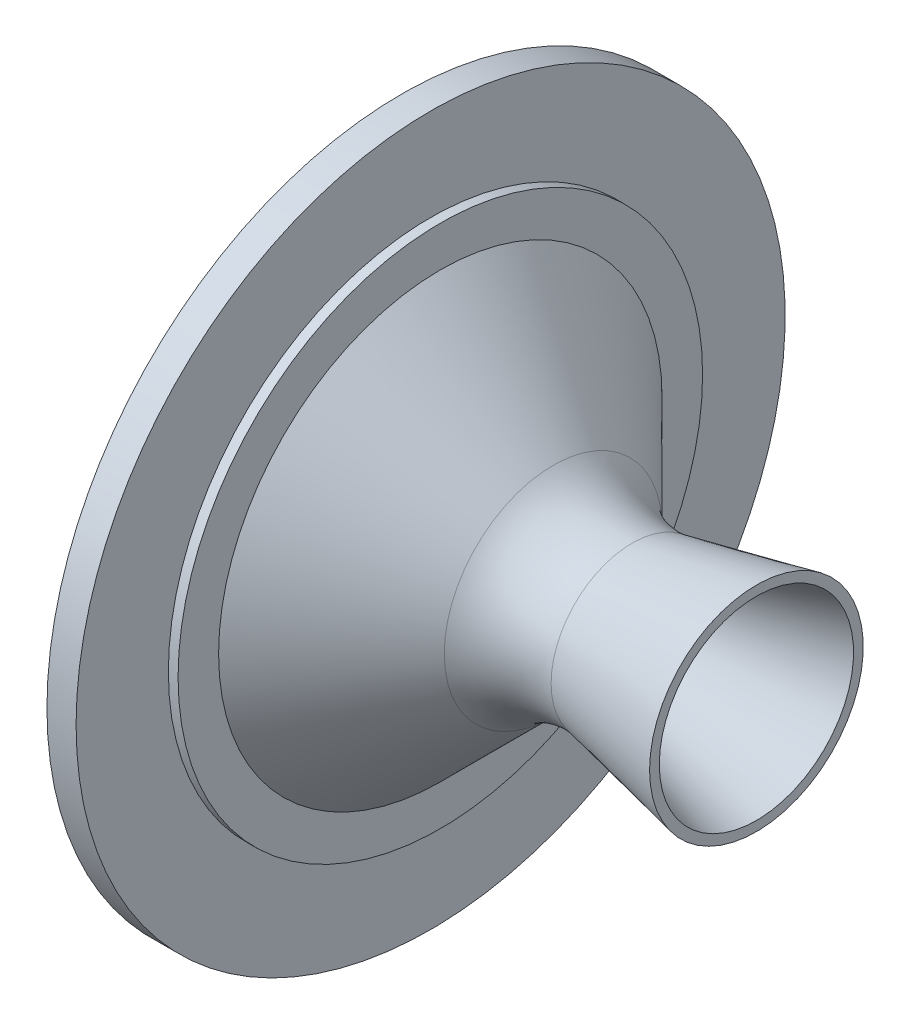
SolidWorks part; units mm, degrees
ref_plane "Plano frontal" through (0, 0, 0) normal (0, 0, 1) x (1, 0, 0)
ref_plane "Plano superior" through (0, 0, 0) normal (0, 1, 0) x (1, 0, 0)
ref_plane "Plano direito" through (0, 0, 0) normal (1, 0, 0) x (0, 0, -1)
ref_axis "eixo de revolução" through (-109.3496, 0, 0) along (1, 0, 0)
sketch "Esboço2" plane through (0, 0, 0) normal (0, 0, 1) x (1, 0, 0)
  line L0 (-38.6301, 24) -> (-36.6301, 24)
  line L1 (-109.3496, 0) -> (68.6304, 0) construction
  line L2 (-36.6301, 24) -> (-36.6301, 22)
  line L3 (-38.6301, 24) -> (-38.6301, 36.5)
  line L4 (-38.6301, 36.5) -> (-35.6301, 36.5)
  line L5 (-35.6301, 36.5) -> (-35.6301, 27)
  line L6 (-35.6301, 27) -> (-34.6301, 27)
  line L7 (-36.6301, 22) -> (-19.5297, 4.9)
  line L8 (-19.5297, 4.9) -> (-2.0891, 10)
  line L9 (-34.6301, 27) -> (-34.6301, 22.8284)
  line L10 (-34.6301, 22.8284) -> (-23.0147, 11.2133)
  line L11 (-14.8801, 8.3434) -> (-2.0891, 11)
  line L12 (-2.0891, 10) -> (-2.0891, 11) construction
  line L13 (-2.0891, 10) -> (-2.0891, 11)
  arc A0 (-23.0147, 11.2133) -> (-14.8801, 8.3434) centre (-15.9457, 18.2865) ccw
  dimension "D8" = 4.9
  dimension "D12" = 10
  dimension "D1" = 24
  dimension "D2" = 2
  dimension "D3" = 22
  dimension "D4" = 12.5
  dimension "D5" = 3
  dimension "D6" = 9.5
  dimension "D7" = 1
  dimension "D9" = 10
  dimension "D10" = 16.3
  dimension "D11" = 2
  dimension "D13" = 51.1
  dimension "D14" = 2
  dimension "D15" = 1
  dimension "D16" = 36.541
  dimension "D17" = 13.064
revolve "revolução" add sketch "Esboço2" angle 360 about axis through (-109.3496, 0, 0) along (1, 0, 0)
